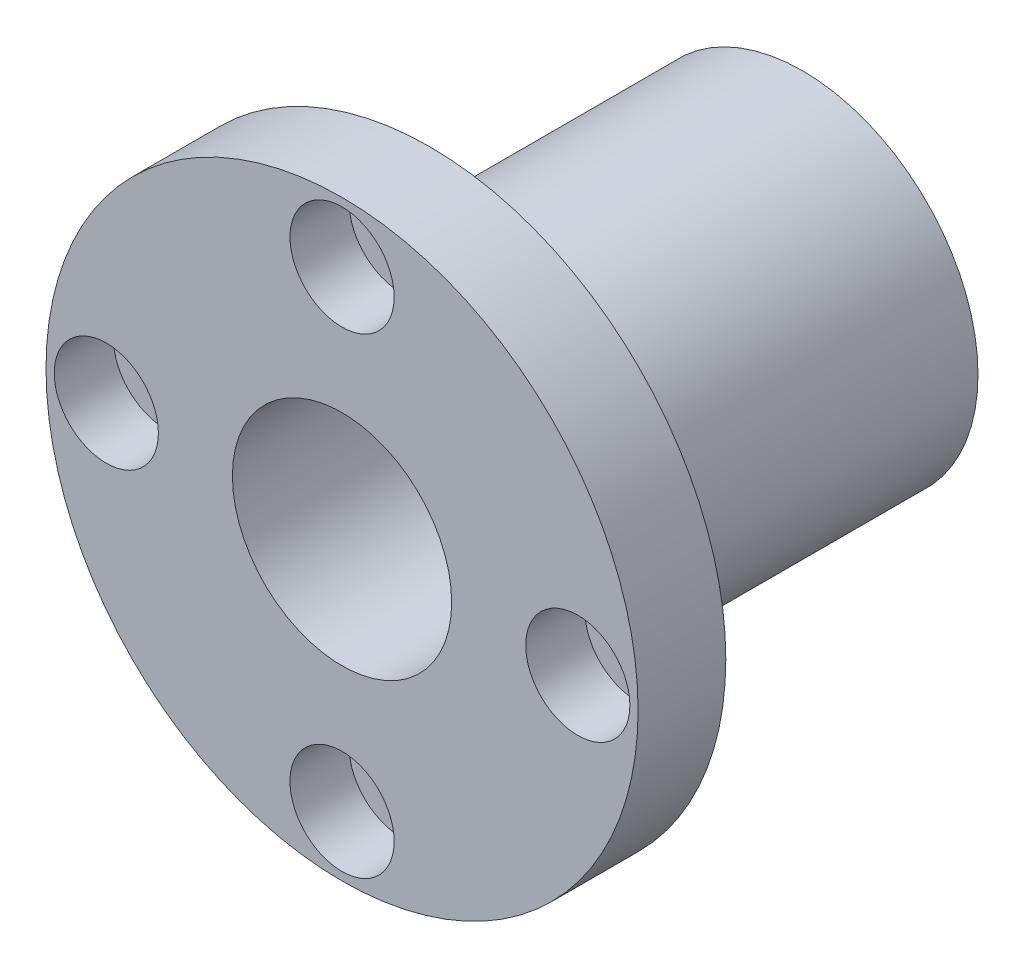
SolidWorks part; units mm, degrees
ref_plane "前视基准面" through (0, 0, 0) normal (0, 0, 1) x (1, 0, 0)
ref_plane "上视基准面" through (0, 0, 0) normal (0, 1, 0) x (1, 0, 0)
ref_plane "右视基准面" through (0, 0, 0) normal (1, 0, 0) x (0, 0, -1)
sketch "草图1" plane through (0, 0, 0) normal (0, -1, 0) x (0, 0, 1)
  line L0 (0, 0) -> (68087.4913, 0) construction
  line L1 (0, 10) -> (42, 10)
  line L2 (42, 10) -> (42, 27)
  line L3 (34, 16) -> (34, 27)
  line L4 (34, 27) -> (42, 27)
  line L11 (34, 16) -> (0, 16)
  line L12 (0, 16) -> (0, 10)
  dimension "D1" = 10
  dimension "D2" = 16
  dimension "D3" = 42
  dimension "D4" = 27
  dimension "D5" = 8
revolve "旋转1" add sketch "草图1" angle 360 about L0
hole_wizard "孔1" positions "草图3" profile "草图2" legacy end condition up to next
sketch "草图3" plane through (0, 0, 42) normal (0, 0, 1) x (1, 0, 0)
  circle A0 centre (0, 0) radius 21.5 construction
  point P0 (0, -21.5)
  point P8 (-21.5, 0)
  point P10 (0, 21.5)
  point P12 (21.5, 0)
  dimension "D1" = 43
sketch "草图2" plane through (0, -21.5, 42) normal (1, 0, 0) x (0, -1, 0)
  line L0 (0, 0) -> (0, 8)
  line L1 (0, 8) -> (2.75, 8)
  line L2 (2.75, 8) -> (2.75, 5.4)
  line L3 (2.75, 5.4) -> (4.75, 5.4)
  line L4 (4.75, 5.4) -> (4.75, 0)
  line L5 (4.75, 0) -> (0, 0)
  line L6 (0, 110) -> (0, -10) construction
  dimension "直径" = 5.5
  dimension "深度" = 8
  dimension "柱坑直径" = 9.5
  dimension "柱坑深度" = 5.4
